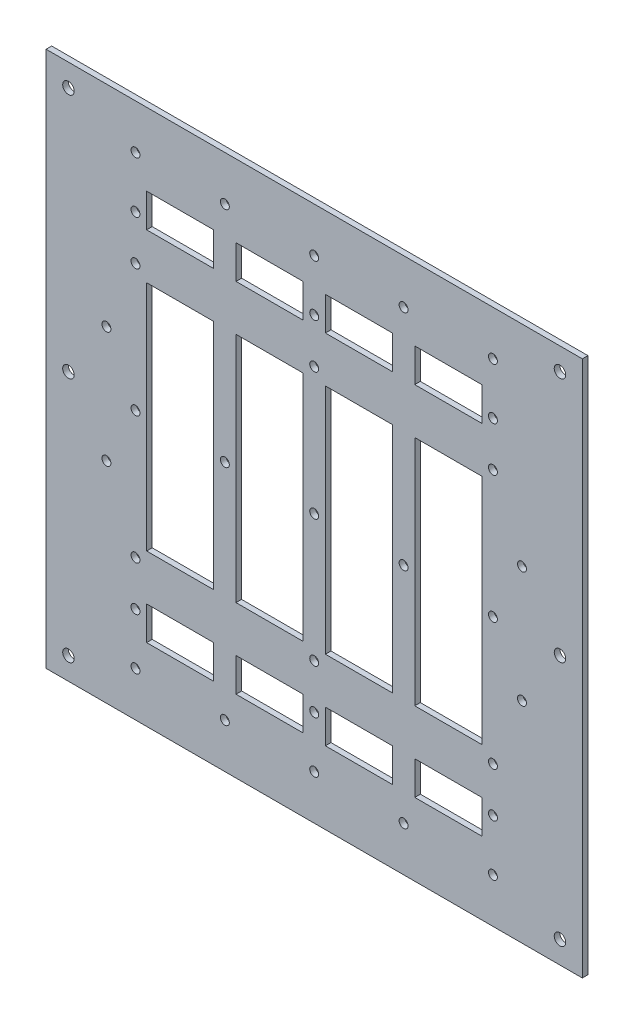
SolidWorks part; units mm, degrees
ref_plane "Front Plane" through (0, 0, 0) normal (0, 0, 1) x (1, 0, 0)
ref_plane "Top Plane" through (0, 0, 0) normal (0, 1, 0) x (1, 0, 0)
ref_plane "Right Plane" through (0, 0, 0) normal (1, 0, 0) x (0, 0, -1)
sketch "Sketch1" plane through (0, 0, 0) normal (0, 0, 1) x (1, 0, 0)
  line L0 (-152.4, 127) -> (-76.2, 127) construction
  line L1 (-152.4, 152.4) -> (152.4, 152.4)
  line L2 (-152.4, 152.4) -> (-152.4, -152.4)
  line L3 (-152.4, -152.4) -> (152.4, -152.4)
  line L4 (152.4, 152.4) -> (152.4, -152.4)
  line L5 (-76.2, 127) -> (-25.4, 127) construction
  line L6 (-25.4, 127) -> (25.4, 127) construction
  line L7 (25.4, 127) -> (76.2, 127) construction
  line L8 (76.2, 127) -> (152.4, 127) construction
  line L9 (-152.4, 0) -> (152.4, 0) construction
  line L10 (0, 152.4) -> (0, -152.4) construction
  line L11 (-118.11, 152.4) -> (-118.11, -152.4) construction
  line L12 (-152.4, -127) -> (152.4, -127) construction
  line L13 (127, 152.4) -> (127, -152.4) construction
  line L14 (-50.8, 152.4) -> (-50.8, -152.4) construction
  line L15 (50.8, 152.4) -> (50.8, -152.4) construction
  line L16 (-101.6, 152.4) -> (-101.6, -152.4) construction
  line L17 (-95.25, 66.04) -> (-57.15, 66.04)
  line L18 (-95.25, 66.04) -> (-95.25, -66.04)
  line L19 (-95.25, -66.04) -> (-57.15, -66.04)
  line L20 (-57.15, 66.04) -> (-57.15, -66.04)
  line L21 (-44.45, 66.04) -> (-6.35, 66.04)
  line L22 (-44.45, 66.04) -> (-44.45, -66.04)
  line L23 (-44.45, -66.04) -> (-6.35, -66.04)
  line L24 (-6.35, 66.04) -> (-6.35, -66.04)
  line L25 (6.35, 66.04) -> (44.45, 66.04)
  line L26 (6.35, 66.04) -> (6.35, -66.04)
  line L27 (6.35, -66.04) -> (44.45, -66.04)
  line L28 (44.45, 66.04) -> (44.45, -66.04)
  line L29 (57.15, 66.04) -> (95.25, 66.04)
  line L30 (57.15, 66.04) -> (57.15, -66.04)
  line L31 (57.15, -66.04) -> (95.25, -66.04)
  line L32 (95.25, 66.04) -> (95.25, -66.04)
  line L33 (101.6, 152.4) -> (101.6, -152.4) construction
  line L34 (-152.4, 120.65) -> (152.4, 120.65) construction
  line L35 (-101.6, 39.7057) -> (-95.25, 39.7057) construction
  line L36 (-57.15, 39.7057) -> (-50.8, 39.7057) construction
  line L37 (-76.2, 66.04) -> (-76.2, 0) construction
  line L38 (-76.2, 0) -> (-76.2, -66.04) construction
  line L39 (-152.4, 72.39) -> (152.4, 72.39) construction
  line L40 (-152.4, -72.39) -> (152.4, -72.39) construction
  line L41 (-76.2, 66.04) -> (-76.2, 72.39) construction
  line L42 (-95.25, -66.04) -> (-95.25, -72.39) construction
  line L43 (95.25, 39.7057) -> (101.6, 39.7057) construction
  line L44 (-95.25, 111.76) -> (-57.15, 111.76) construction
  line L45 (-57.15, 111.76) -> (-57.15, 118.4779) construction
  line L46 (-94.0266, 120.65) -> (-78.1749, 130.2582) construction
  line L47 (-95.25, 111.76) -> (-95.25, 118.4779) construction
  line L48 (-58.3734, 120.65) -> (-74.2251, 130.2582) construction
  line L49 (-107.3169, 130.81) -> (-83.1894, 130.81) construction
  line L50 (-6.35, 111.76) -> (-6.35, 118.4779) construction
  line L51 (-7.5734, 120.65) -> (-23.4251, 130.2582) construction
  line L52 (-43.2266, 120.65) -> (-27.3749, 130.2582) construction
  line L53 (-44.45, 111.76) -> (-44.45, 118.4779) construction
  line L54 (-6.35, 111.76) -> (-44.45, 111.76) construction
  line L55 (44.45, 111.76) -> (44.45, 118.4779) construction
  line L56 (43.2266, 120.65) -> (27.3749, 130.2582) construction
  line L57 (7.5734, 120.65) -> (23.4251, 130.2582) construction
  line L58 (6.35, 111.76) -> (6.35, 118.4779) construction
  line L59 (6.35, 111.76) -> (44.45, 111.76) construction
  line L60 (95.25, 111.76) -> (57.15, 111.76) construction
  line L61 (95.25, 111.76) -> (95.25, 118.4779) construction
  line L62 (94.0266, 120.65) -> (78.1749, 130.2582) construction
  line L63 (58.3734, 120.65) -> (74.2251, 130.2582) construction
  line L64 (57.15, 111.76) -> (57.15, 118.4779) construction
  line L65 (-95.25, -111.76) -> (-95.25, -118.4779) construction
  line L66 (-94.0266, -120.65) -> (-78.1749, -130.2582) construction
  line L67 (-58.3734, -120.65) -> (-74.2251, -130.2582) construction
  line L68 (-95.25, -111.76) -> (-57.15, -111.76) construction
  line L69 (-57.15, -111.76) -> (-57.15, -118.4779) construction
  line L70 (-44.45, -111.76) -> (-44.45, -118.4779) construction
  line L71 (-43.2266, -120.65) -> (-27.3749, -130.2582) construction
  line L72 (-6.35, -111.76) -> (-44.45, -111.76) construction
  line L73 (-7.5734, -120.65) -> (-23.4251, -130.2582) construction
  line L74 (-6.35, -111.76) -> (-6.35, -118.4779) construction
  line L75 (6.35, -111.76) -> (6.35, -118.4779) construction
  line L76 (7.5734, -120.65) -> (23.4251, -130.2582) construction
  line L77 (43.2266, -120.65) -> (27.3749, -130.2582) construction
  line L78 (6.35, -111.76) -> (44.45, -111.76) construction
  line L79 (44.45, -111.76) -> (44.45, -118.4779) construction
  line L80 (57.15, -111.76) -> (57.15, -118.4779) construction
  line L81 (58.3734, -120.65) -> (74.2251, -130.2582) construction
  line L82 (94.0266, -120.65) -> (78.1749, -130.2582) construction
  line L83 (95.25, -111.76) -> (57.15, -111.76) construction
  line L84 (95.25, -111.76) -> (95.25, -118.4779) construction
  line L85 (-152.4, 97.79) -> (152.4, 97.79) construction
  line L86 (-50.8, 39.7057) -> (-44.45, 39.7057) construction
  line L87 (-127, 152.4) -> (-127, -152.4) construction
  line L89 (-95.25, 101.6) -> (-92.3192, 101.6) construction
  line L90 (-95.25, 101.6) -> (-95.25, -101.6) construction
  line L96 (-90.8538, 101.6) -> (-90.8538, 68.58) construction
  line L97 (-89.3885, 101.6) -> (-89.3885, 68.58) construction
  line L98 (-92.3192, 101.6) -> (-92.3192, 68.58) construction
  line L99 (-83.5269, 101.6) -> (-83.5269, 68.58) construction
  line L100 (-86.4577, 101.6) -> (-86.4577, 68.58) construction
  line L101 (-89.3885, 101.6) -> (-86.4577, 101.6) construction
  line L102 (-77.6654, 101.6) -> (-77.6654, 68.58) construction
  line L103 (-80.5962, 101.6) -> (-80.5962, 68.58) construction
  line L104 (-83.5269, 101.6) -> (-80.5962, 101.6) construction
  line L105 (-71.8038, 101.6) -> (-71.8038, 68.58) construction
  line L106 (-74.7346, 101.6) -> (-74.7346, 68.58) construction
  line L107 (-77.6654, 101.6) -> (-74.7346, 101.6) construction
  line L108 (-65.9423, 101.6) -> (-65.9423, 68.58) construction
  line L109 (-68.8731, 101.6) -> (-68.8731, 68.58) construction
  line L110 (-71.8038, 101.6) -> (-68.8731, 101.6) construction
  line L111 (-60.0808, 101.6) -> (-60.0808, 68.58) construction
  line L112 (-63.0115, 101.6) -> (-63.0115, 68.58) construction
  line L113 (-65.9423, 101.6) -> (-63.0115, 101.6) construction
  line L114 (-57.15, -101.6) -> (-57.15, 101.6) construction
  line L115 (-60.0808, 101.6) -> (-57.15, 101.6) construction
  line L116 (-92.3192, 68.58) -> (-89.3885, 68.58) construction
  line L117 (-60.0808, -101.6) -> (-57.15, -101.6) construction
  line L118 (-60.0808, -101.6) -> (-60.0808, -68.58) construction
  line L119 (-63.0115, -101.6) -> (-63.0115, -68.58) construction
  line L120 (-65.9423, -101.6) -> (-65.9423, -68.58) construction
  line L121 (-65.9423, -101.6) -> (-63.0115, -101.6) construction
  line L122 (-68.8731, -101.6) -> (-68.8731, -68.58) construction
  line L123 (-71.8038, -101.6) -> (-68.8731, -101.6) construction
  line L124 (-71.8038, -101.6) -> (-71.8038, -68.58) construction
  line L125 (-74.7346, -101.6) -> (-74.7346, -68.58) construction
  line L126 (-77.6654, -101.6) -> (-74.7346, -101.6) construction
  line L127 (-77.6654, -101.6) -> (-77.6654, -68.58) construction
  line L128 (-80.5962, -101.6) -> (-80.5962, -68.58) construction
  line L129 (-83.5269, -101.6) -> (-80.5962, -101.6) construction
  line L130 (-83.5269, -101.6) -> (-83.5269, -68.58) construction
  line L131 (-86.4577, -101.6) -> (-86.4577, -68.58) construction
  line L132 (-89.3885, -101.6) -> (-86.4577, -101.6) construction
  line L133 (-89.3885, -101.6) -> (-89.3885, -68.58) construction
  line L134 (-92.3192, -101.6) -> (-92.3192, -68.58) construction
  line L135 (-95.25, -101.6) -> (-92.3192, -101.6) construction
  line L136 (-9.2808, 68.58) -> (-12.2115, 68.58) construction
  line L137 (6.35, 66.04) -> (44.45, 66.04) construction
  line L138 (-6.35, -66.04) -> (-6.35, -72.39) construction
  line L139 (-25.4, 66.04) -> (-25.4, 72.39) construction
  line L140 (-25.4, 0) -> (-25.4, -66.04) construction
  line L141 (-25.4, 66.04) -> (-25.4, 0) construction
  line L142 (-44.45, 66.04) -> (-44.45, -66.04) construction
  line L143 (-6.35, -66.04) -> (-44.45, -66.04) construction
  line L144 (-6.35, 66.04) -> (-6.35, -66.04) construction
  line L145 (-6.35, 66.04) -> (-44.45, 66.04) construction
  line L146 (-6.35, -101.6) -> (-9.2808, -101.6) construction
  line L147 (-9.2808, -101.6) -> (-9.2808, -68.58) construction
  line L148 (-12.2115, -101.6) -> (-12.2115, -68.58) construction
  line L149 (-12.2115, -101.6) -> (-15.1423, -101.6) construction
  line L150 (-15.1423, -101.6) -> (-15.1423, -68.58) construction
  line L151 (-18.0731, -101.6) -> (-18.0731, -68.58) construction
  line L152 (-18.0731, -101.6) -> (-21.0038, -101.6) construction
  line L153 (-21.0038, -101.6) -> (-21.0038, -68.58) construction
  line L154 (-23.9346, -101.6) -> (-23.9346, -68.58) construction
  line L155 (-23.9346, -101.6) -> (-26.8654, -101.6) construction
  line L156 (-26.8654, -101.6) -> (-26.8654, -68.58) construction
  line L157 (-29.7962, -101.6) -> (-29.7962, -68.58) construction
  line L158 (-29.7962, -101.6) -> (-32.7269, -101.6) construction
  line L159 (-32.7269, -101.6) -> (-32.7269, -68.58) construction
  line L160 (-35.6577, -101.6) -> (-38.5885, -101.6) construction
  line L161 (-35.6577, -101.6) -> (-35.6577, -68.58) construction
  line L162 (-38.5885, -101.6) -> (-38.5885, -68.58) construction
  line L163 (-41.5192, -101.6) -> (-41.5192, -68.58) construction
  line L164 (-41.5192, -101.6) -> (-44.45, -101.6) construction
  line L165 (-41.5192, 101.6) -> (-44.45, 101.6) construction
  line L166 (-44.45, -101.6) -> (-44.45, 101.6) construction
  line L167 (-35.6577, 101.6) -> (-38.5885, 101.6) construction
  line L168 (-38.5885, 101.6) -> (-38.5885, 68.58) construction
  line L169 (-41.5192, 101.6) -> (-41.5192, 68.58) construction
  line L170 (-29.7962, 101.6) -> (-32.7269, 101.6) construction
  line L171 (-32.7269, 101.6) -> (-32.7269, 68.58) construction
  line L172 (-35.6577, 101.6) -> (-35.6577, 68.58) construction
  line L173 (-23.9346, 101.6) -> (-26.8654, 101.6) construction
  line L174 (-26.8654, 101.6) -> (-26.8654, 68.58) construction
  line L175 (-29.7962, 101.6) -> (-29.7962, 68.58) construction
  line L176 (-18.0731, 101.6) -> (-21.0038, 101.6) construction
  line L177 (-21.0038, 101.6) -> (-21.0038, 68.58) construction
  line L178 (-23.9346, 101.6) -> (-23.9346, 68.58) construction
  line L179 (-12.2115, 101.6) -> (-15.1423, 101.6) construction
  line L180 (-15.1423, 101.6) -> (-15.1423, 68.58) construction
  line L181 (-18.0731, 101.6) -> (-18.0731, 68.58) construction
  line L182 (-9.2808, 101.6) -> (-9.2808, 68.58) construction
  line L183 (-12.2115, 101.6) -> (-12.2115, 68.58) construction
  line L184 (-6.35, 101.6) -> (-6.35, -101.6) construction
  line L185 (-6.35, 101.6) -> (-9.2808, 101.6) construction
  line L186 (6.35, 66.04) -> (6.35, -66.04) construction
  line L187 (6.35, -66.04) -> (44.45, -66.04) construction
  line L188 (44.45, 66.04) -> (44.45, -66.04) construction
  line L189 (25.4, 66.04) -> (25.4, 0) construction
  line L190 (25.4, 0) -> (25.4, -66.04) construction
  line L191 (25.4, 66.04) -> (25.4, 72.39) construction
  line L192 (6.35, -66.04) -> (6.35, -72.39) construction
  line L193 (9.2808, 68.58) -> (12.2115, 68.58) construction
  line L194 (6.35, 66.04) -> (6.35, -66.04) construction
  line L195 (44.45, -66.04) -> (6.35, -66.04) construction
  line L196 (44.45, 66.04) -> (44.45, -66.04) construction
  line L197 (44.45, 66.04) -> (6.35, 66.04) construction
  line L198 (6.35, 101.6) -> (9.2808, 101.6) construction
  line L199 (6.35, 101.6) -> (6.35, -101.6) construction
  line L200 (12.2115, 101.6) -> (12.2115, 68.58) construction
  line L201 (9.2808, 101.6) -> (9.2808, 68.58) construction
  line L202 (18.0731, 101.6) -> (18.0731, 68.58) construction
  line L203 (15.1423, 101.6) -> (15.1423, 68.58) construction
  line L204 (12.2115, 101.6) -> (15.1423, 101.6) construction
  line L205 (23.9346, 101.6) -> (23.9346, 68.58) construction
  line L206 (21.0038, 101.6) -> (21.0038, 68.58) construction
  line L207 (18.0731, 101.6) -> (21.0038, 101.6) construction
  line L208 (29.7962, 101.6) -> (29.7962, 68.58) construction
  line L209 (26.8654, 101.6) -> (26.8654, 68.58) construction
  line L210 (23.9346, 101.6) -> (26.8654, 101.6) construction
  line L211 (35.6577, 101.6) -> (35.6577, 68.58) construction
  line L212 (32.7269, 101.6) -> (32.7269, 68.58) construction
  line L213 (29.7962, 101.6) -> (32.7269, 101.6) construction
  line L214 (41.5192, 101.6) -> (41.5192, 68.58) construction
  line L215 (38.5885, 101.6) -> (38.5885, 68.58) construction
  line L216 (35.6577, 101.6) -> (38.5885, 101.6) construction
  line L217 (44.45, -101.6) -> (44.45, 101.6) construction
  line L218 (41.5192, 101.6) -> (44.45, 101.6) construction
  line L219 (41.5192, -101.6) -> (44.45, -101.6) construction
  line L220 (41.5192, -101.6) -> (41.5192, -68.58) construction
  line L221 (38.5885, -101.6) -> (38.5885, -68.58) construction
  line L222 (35.6577, -101.6) -> (35.6577, -68.58) construction
  line L223 (35.6577, -101.6) -> (38.5885, -101.6) construction
  line L224 (32.7269, -101.6) -> (32.7269, -68.58) construction
  line L225 (29.7962, -101.6) -> (32.7269, -101.6) construction
  line L226 (29.7962, -101.6) -> (29.7962, -68.58) construction
  line L227 (26.8654, -101.6) -> (26.8654, -68.58) construction
  line L228 (23.9346, -101.6) -> (26.8654, -101.6) construction
  line L229 (23.9346, -101.6) -> (23.9346, -68.58) construction
  line L230 (21.0038, -101.6) -> (21.0038, -68.58) construction
  line L231 (18.0731, -101.6) -> (21.0038, -101.6) construction
  line L232 (18.0731, -101.6) -> (18.0731, -68.58) construction
  line L233 (15.1423, -101.6) -> (15.1423, -68.58) construction
  line L234 (12.2115, -101.6) -> (15.1423, -101.6) construction
  line L235 (12.2115, -101.6) -> (12.2115, -68.58) construction
  line L236 (9.2808, -101.6) -> (9.2808, -68.58) construction
  line L237 (6.35, -101.6) -> (9.2808, -101.6) construction
  line L238 (57.15, 66.04) -> (95.25, 66.04) construction
  line L239 (57.15, 66.04) -> (57.15, -66.04) construction
  line L240 (57.15, -66.04) -> (95.25, -66.04) construction
  line L241 (95.25, 66.04) -> (95.25, -66.04) construction
  line L242 (92.3192, 68.58) -> (89.3885, 68.58) construction
  line L243 (95.25, -66.04) -> (95.25, -72.39) construction
  line L244 (76.2, 66.04) -> (76.2, 72.39) construction
  line L245 (76.2, 0) -> (76.2, -66.04) construction
  line L246 (76.2, 66.04) -> (76.2, 0) construction
  line L247 (57.15, 66.04) -> (57.15, -66.04) construction
  line L248 (95.25, -66.04) -> (57.15, -66.04) construction
  line L249 (95.25, 66.04) -> (95.25, -66.04) construction
  line L250 (95.25, 66.04) -> (57.15, 66.04) construction
  line L251 (57.15, 66.04) -> (57.15, -66.04) construction
  line L252 (95.25, -66.04) -> (57.15, -66.04) construction
  line L253 (95.25, 66.04) -> (95.25, -66.04) construction
  line L254 (95.25, 66.04) -> (57.15, 66.04) construction
  line L255 (95.25, -101.6) -> (92.3192, -101.6) construction
  line L256 (92.3192, -101.6) -> (92.3192, -68.58) construction
  line L257 (89.3885, -101.6) -> (89.3885, -68.58) construction
  line L258 (89.3885, -101.6) -> (86.4577, -101.6) construction
  line L259 (86.4577, -101.6) -> (86.4577, -68.58) construction
  line L260 (83.5269, -101.6) -> (83.5269, -68.58) construction
  line L261 (83.5269, -101.6) -> (80.5962, -101.6) construction
  line L262 (80.5962, -101.6) -> (80.5962, -68.58) construction
  line L263 (77.6654, -101.6) -> (77.6654, -68.58) construction
  line L264 (77.6654, -101.6) -> (74.7346, -101.6) construction
  line L265 (74.7346, -101.6) -> (74.7346, -68.58) construction
  line L266 (71.8038, -101.6) -> (71.8038, -68.58) construction
  line L267 (71.8038, -101.6) -> (68.8731, -101.6) construction
  line L268 (68.8731, -101.6) -> (68.8731, -68.58) construction
  line L269 (65.9423, -101.6) -> (63.0115, -101.6) construction
  line L270 (65.9423, -101.6) -> (65.9423, -68.58) construction
  line L271 (63.0115, -101.6) -> (63.0115, -68.58) construction
  line L272 (60.0808, -101.6) -> (60.0808, -68.58) construction
  line L273 (60.0808, -101.6) -> (57.15, -101.6) construction
  line L274 (60.0808, 101.6) -> (57.15, 101.6) construction
  line L275 (57.15, -101.6) -> (57.15, 101.6) construction
  line L276 (65.9423, 101.6) -> (63.0115, 101.6) construction
  line L277 (63.0115, 101.6) -> (63.0115, 68.58) construction
  line L278 (60.0808, 101.6) -> (60.0808, 68.58) construction
  line L279 (71.8038, 101.6) -> (68.8731, 101.6) construction
  line L280 (68.8731, 101.6) -> (68.8731, 68.58) construction
  line L281 (65.9423, 101.6) -> (65.9423, 68.58) construction
  line L282 (77.6654, 101.6) -> (74.7346, 101.6) construction
  line L283 (74.7346, 101.6) -> (74.7346, 68.58) construction
  line L284 (71.8038, 101.6) -> (71.8038, 68.58) construction
  line L285 (83.5269, 101.6) -> (80.5962, 101.6) construction
  line L286 (80.5962, 101.6) -> (80.5962, 68.58) construction
  line L287 (77.6654, 101.6) -> (77.6654, 68.58) construction
  line L288 (89.3885, 101.6) -> (86.4577, 101.6) construction
  line L289 (86.4577, 101.6) -> (86.4577, 68.58) construction
  line L290 (83.5269, 101.6) -> (83.5269, 68.58) construction
  line L291 (92.3192, 101.6) -> (92.3192, 68.58) construction
  line L292 (89.3885, 101.6) -> (89.3885, 68.58) construction
  line L293 (95.25, 101.6) -> (95.25, -101.6) construction
  line L294 (95.25, 101.6) -> (92.3192, 101.6) construction
  line L295 (-101.6, 39.7057) -> (-107.95, 39.7057) construction
  line L296 (-101.6, 78.74) -> (101.6, 78.74) construction
  line L297 (-107.95, 72.39) -> (-107.95, -72.39) construction
  line L298 (-101.6, -78.74) -> (101.6, -78.74) construction
  line L299 (107.95, 72.39) -> (107.95, -72.39) construction
  line L300 (-97.0611, 78.74) -> (-97.0611, 72.39) construction
  line L301 (-107.95, 22.225) -> (-120.65, 22.225) construction
  line L302 (-127, 15.875) -> (-127, -15.875) construction
  line L303 (-120.65, -22.225) -> (-107.95, -22.225) construction
  line L304 (-90.964, 120.65) -> (-61.436, 120.65) construction
  line L305 (-90.964, 122.2375) -> (-61.436, 122.2375) construction
  line L306 (-90.964, 119.0625) -> (-61.436, 119.0625) construction
  line L307 (-10.636, 120.65) -> (-40.164, 120.65) construction
  line L308 (-10.636, 122.2375) -> (-40.164, 122.2375) construction
  line L309 (-10.636, 119.0625) -> (-40.164, 119.0625) construction
  line L310 (10.636, 120.65) -> (40.164, 120.65) construction
  line L311 (10.636, 122.2375) -> (40.164, 122.2375) construction
  line L312 (10.636, 119.0625) -> (40.164, 119.0625) construction
  line L313 (90.964, 120.65) -> (61.436, 120.65) construction
  line L314 (90.964, 122.2375) -> (61.436, 122.2375) construction
  line L315 (90.964, 119.0625) -> (61.436, 119.0625) construction
  line L316 (90.964, -120.65) -> (61.436, -120.65) construction
  line L317 (90.964, -122.2375) -> (61.436, -122.2375) construction
  line L318 (90.964, -119.0625) -> (61.436, -119.0625) construction
  line L319 (10.636, -120.65) -> (40.164, -120.65) construction
  line L320 (10.636, -122.2375) -> (40.164, -122.2375) construction
  line L321 (10.636, -119.0625) -> (40.164, -119.0625) construction
  line L322 (-10.636, -120.65) -> (-40.164, -120.65) construction
  line L323 (-10.636, -122.2375) -> (-40.164, -122.2375) construction
  line L324 (-10.636, -119.0625) -> (-40.164, -119.0625) construction
  line L325 (-90.964, -120.65) -> (-61.436, -120.65) construction
  line L326 (-90.964, -122.2375) -> (-61.436, -122.2375) construction
  line L327 (-90.964, -119.0625) -> (-61.436, -119.0625) construction
  line L328 (-6.35, 111.125) -> (-6.35, 92.075)
  line L329 (-95.25, 111.125) -> (-57.15, 111.125)
  line L330 (-95.25, 111.125) -> (-95.25, 92.075)
  line L331 (-95.25, 92.075) -> (-57.15, 92.075)
  line L332 (-57.15, 111.125) -> (-57.15, 92.075)
  line L333 (-6.35, 111.125) -> (-44.45, 111.125)
  line L334 (-44.45, 111.125) -> (-44.45, 92.075)
  line L335 (-6.35, 92.075) -> (-44.45, 92.075)
  line L336 (95.25, 92.075) -> (57.15, 92.075)
  line L337 (95.25, 111.125) -> (95.25, 92.075)
  line L338 (95.25, 111.125) -> (57.15, 111.125)
  line L339 (57.15, 111.125) -> (57.15, 92.075)
  line L340 (44.45, 111.125) -> (44.45, 92.075)
  line L341 (6.35, 92.075) -> (44.45, 92.075)
  line L342 (6.35, 111.125) -> (44.45, 111.125)
  line L343 (6.35, 111.125) -> (6.35, 92.075)
  line L344 (-95.25, -92.075) -> (-57.15, -92.075)
  line L345 (-95.25, -111.125) -> (-95.25, -92.075)
  line L346 (-95.25, -111.125) -> (-57.15, -111.125)
  line L347 (-57.15, -111.125) -> (-57.15, -92.075)
  line L348 (-44.45, -111.125) -> (-44.45, -92.075)
  line L349 (-6.35, -92.075) -> (-44.45, -92.075)
  line L350 (-6.35, -111.125) -> (-44.45, -111.125)
  line L351 (-6.35, -111.125) -> (-6.35, -92.075)
  line L352 (6.35, -111.125) -> (6.35, -92.075)
  line L353 (6.35, -92.075) -> (44.45, -92.075)
  line L354 (6.35, -111.125) -> (44.45, -111.125)
  line L355 (44.45, -111.125) -> (44.45, -92.075)
  line L356 (57.15, -111.125) -> (57.15, -92.075)
  line L357 (95.25, -111.125) -> (57.15, -111.125)
  line L358 (95.25, -111.125) -> (95.25, -92.075)
  line L359 (95.25, -92.075) -> (57.15, -92.075)
  circle A0 centre (-76.2, 127) radius 2.5527 construction
  circle A1 centre (-25.4, 127) radius 2.5527 construction
  circle A2 centre (25.4, 127) radius 2.5527 construction
  circle A3 centre (76.2, 127) radius 2.5527 construction
  circle A4 centre (-101.6, 0) radius 2.54
  circle A5 centre (-50.8, 0) radius 2.54
  circle A6 centre (0, 0) radius 2.54
  circle A7 centre (101.6, 0) radius 2.54
  circle A8 centre (50.8, 0) radius 2.54
  circle A9 centre (-50.8, 127) radius 2.54
  circle A10 centre (0, 127) radius 2.54
  circle A11 centre (50.8, 127) radius 2.54
  circle A12 centre (-101.6, 72.39) radius 2.54
  circle A13 centre (0, 72.39) radius 2.54
  circle A14 centre (101.6, 72.39) radius 2.54
  circle A15 centre (-101.6, -72.39) radius 2.54
  circle A16 centre (0, -72.39) radius 2.54
  circle A17 centre (101.6, -72.39) radius 2.54
  arc A18 (-74.2251, 130.2582) -> (-78.1749, 130.2582) centre (-76.2, 127) ccw construction
  arc A19 (-57.15, 118.4779) -> (-58.3734, 120.65) centre (-59.69, 118.4779) ccw construction
  arc A20 (-95.25, 118.4779) -> (-94.0266, 120.65) centre (-92.71, 118.4779) cw construction
  arc A21 (-6.35, 118.4779) -> (-7.5734, 120.65) centre (-8.89, 118.4779) ccw construction
  arc A22 (-27.3749, 130.2582) -> (-23.4251, 130.2582) centre (-25.4, 127) cw construction
  arc A23 (-44.45, 118.4779) -> (-43.2266, 120.65) centre (-41.91, 118.4779) cw construction
  arc A24 (44.45, 118.4779) -> (43.2266, 120.65) centre (41.91, 118.4779) ccw construction
  arc A25 (27.3749, 130.2582) -> (23.4251, 130.2582) centre (25.4, 127) ccw construction
  arc A26 (6.35, 118.4779) -> (7.5734, 120.65) centre (8.89, 118.4779) cw construction
  arc A27 (95.25, 118.4779) -> (94.0266, 120.65) centre (92.71, 118.4779) ccw construction
  arc A28 (74.2251, 130.2582) -> (78.1749, 130.2582) centre (76.2, 127) cw construction
  arc A29 (57.15, 118.4779) -> (58.3734, 120.65) centre (59.69, 118.4779) cw construction
  circle A30 centre (-76.2, -127) radius 2.5527 construction
  circle A31 centre (-25.4, -127) radius 2.5527 construction
  circle A32 centre (25.4, -127) radius 2.5527 construction
  circle A33 centre (76.2, -127) radius 2.5527 construction
  arc A34 (-95.25, -118.4779) -> (-94.0266, -120.65) centre (-92.71, -118.4779) ccw construction
  arc A35 (-74.2251, -130.2582) -> (-78.1749, -130.2582) centre (-76.2, -127) cw construction
  arc A36 (-57.15, -118.4779) -> (-58.3734, -120.65) centre (-59.69, -118.4779) cw construction
  arc A37 (-44.45, -118.4779) -> (-43.2266, -120.65) centre (-41.91, -118.4779) ccw construction
  arc A38 (-27.3749, -130.2582) -> (-23.4251, -130.2582) centre (-25.4, -127) ccw construction
  arc A39 (-6.35, -118.4779) -> (-7.5734, -120.65) centre (-8.89, -118.4779) cw construction
  arc A40 (6.35, -118.4779) -> (7.5734, -120.65) centre (8.89, -118.4779) ccw construction
  arc A41 (27.3749, -130.2582) -> (23.4251, -130.2582) centre (25.4, -127) cw construction
  arc A42 (44.45, -118.4779) -> (43.2266, -120.65) centre (41.91, -118.4779) cw construction
  arc A43 (57.15, -118.4779) -> (58.3734, -120.65) centre (59.69, -118.4779) ccw construction
  arc A44 (74.2251, -130.2582) -> (78.1749, -130.2582) centre (76.2, -127) ccw construction
  arc A45 (95.25, -118.4779) -> (94.0266, -120.65) centre (92.71, -118.4779) cw construction
  circle A46 centre (50.8, -127) radius 2.54
  circle A47 centre (0, -127) radius 2.54
  circle A48 centre (-50.8, -127) radius 2.54
  circle A49 centre (-101.6, 97.79) radius 2.54
  circle A50 centre (0, 97.79) radius 2.54
  circle A51 centre (101.6, 97.79) radius 2.54
  circle A52 centre (101.6, 127) radius 2.54
  circle A53 centre (-101.6, 127) radius 2.54
  circle A54 centre (-118.11, 33.02) radius 2.54
  circle A56 centre (-101.6, -127) radius 2.54
  circle A57 centre (101.6, -127) radius 2.54
  circle A58 centre (101.6, -97.79) radius 2.54
  circle A59 centre (0, -97.79) radius 2.54
  circle A60 centre (-101.6, -97.79) radius 2.54
  circle A61 centre (-118.11, -33.02) radius 2.54
  circle A63 centre (-139.7, 139.7) radius 3.2639
  circle A64 centre (-139.7, 0) radius 3.2639
  circle A65 centre (-139.7, -139.7) radius 3.2639
  circle A66 centre (139.7, -139.7) radius 3.2639
  circle A67 centre (139.7, 0) radius 3.2639
  circle A68 centre (139.7, 139.7) radius 3.2639
  arc A70 (-92.3192, 68.58) -> (-89.3885, 68.58) centre (-90.8538, 68.58) ccw construction
  arc A71 (-86.4577, 68.58) -> (-83.5269, 68.58) centre (-84.9923, 68.58) ccw construction
  arc A72 (-80.5962, 68.58) -> (-77.6654, 68.58) centre (-79.1308, 68.58) ccw construction
  arc A73 (-74.7346, 68.58) -> (-71.8038, 68.58) centre (-73.2692, 68.58) ccw construction
  arc A74 (-68.8731, 68.58) -> (-65.9423, 68.58) centre (-67.4077, 68.58) ccw construction
  arc A75 (-63.0115, 68.58) -> (-60.0808, 68.58) centre (-61.5462, 68.58) ccw construction
  arc A76 (-63.0115, -68.58) -> (-60.0808, -68.58) centre (-61.5462, -68.58) cw construction
  arc A77 (-68.8731, -68.58) -> (-65.9423, -68.58) centre (-67.4077, -68.58) cw construction
  arc A78 (-74.7346, -68.58) -> (-71.8038, -68.58) centre (-73.2692, -68.58) cw construction
  arc A79 (-80.5962, -68.58) -> (-77.6654, -68.58) centre (-79.1308, -68.58) cw construction
  arc A80 (-86.4577, -68.58) -> (-83.5269, -68.58) centre (-84.9923, -68.58) cw construction
  arc A81 (-92.3192, -68.58) -> (-89.3885, -68.58) centre (-90.8538, -68.58) cw construction
  arc A82 (-9.2808, -68.58) -> (-12.2115, -68.58) centre (-10.7462, -68.58) ccw construction
  arc A83 (-15.1423, -68.58) -> (-18.0731, -68.58) centre (-16.6077, -68.58) ccw construction
  arc A84 (-21.0038, -68.58) -> (-23.9346, -68.58) centre (-22.4692, -68.58) ccw construction
  arc A85 (-26.8654, -68.58) -> (-29.7962, -68.58) centre (-28.3308, -68.58) ccw construction
  arc A86 (-32.7269, -68.58) -> (-35.6577, -68.58) centre (-34.1923, -68.58) ccw construction
  arc A87 (-38.5885, -68.58) -> (-41.5192, -68.58) centre (-40.0538, -68.58) ccw construction
  arc A88 (-38.5885, 68.58) -> (-41.5192, 68.58) centre (-40.0538, 68.58) cw construction
  arc A89 (-32.7269, 68.58) -> (-35.6577, 68.58) centre (-34.1923, 68.58) cw construction
  arc A90 (-26.8654, 68.58) -> (-29.7962, 68.58) centre (-28.3308, 68.58) cw construction
  arc A91 (-21.0038, 68.58) -> (-23.9346, 68.58) centre (-22.4692, 68.58) cw construction
  arc A92 (-15.1423, 68.58) -> (-18.0731, 68.58) centre (-16.6077, 68.58) cw construction
  arc A93 (-9.2808, 68.58) -> (-12.2115, 68.58) centre (-10.7462, 68.58) cw construction
  arc A94 (9.2808, 68.58) -> (12.2115, 68.58) centre (10.7462, 68.58) ccw construction
  arc A95 (15.1423, 68.58) -> (18.0731, 68.58) centre (16.6077, 68.58) ccw construction
  arc A96 (21.0038, 68.58) -> (23.9346, 68.58) centre (22.4692, 68.58) ccw construction
  arc A97 (26.8654, 68.58) -> (29.7962, 68.58) centre (28.3308, 68.58) ccw construction
  arc A98 (32.7269, 68.58) -> (35.6577, 68.58) centre (34.1923, 68.58) ccw construction
  arc A99 (38.5885, 68.58) -> (41.5192, 68.58) centre (40.0538, 68.58) ccw construction
  arc A100 (38.5885, -68.58) -> (41.5192, -68.58) centre (40.0538, -68.58) cw construction
  arc A101 (32.7269, -68.58) -> (35.6577, -68.58) centre (34.1923, -68.58) cw construction
  arc A102 (26.8654, -68.58) -> (29.7962, -68.58) centre (28.3308, -68.58) cw construction
  arc A103 (21.0038, -68.58) -> (23.9346, -68.58) centre (22.4692, -68.58) cw construction
  arc A104 (15.1423, -68.58) -> (18.0731, -68.58) centre (16.6077, -68.58) cw construction
  arc A105 (9.2808, -68.58) -> (12.2115, -68.58) centre (10.7462, -68.58) cw construction
  arc A106 (92.3192, -68.58) -> (89.3885, -68.58) centre (90.8538, -68.58) ccw construction
  arc A107 (86.4577, -68.58) -> (83.5269, -68.58) centre (84.9923, -68.58) ccw construction
  arc A108 (80.5962, -68.58) -> (77.6654, -68.58) centre (79.1308, -68.58) ccw construction
  arc A109 (74.7346, -68.58) -> (71.8038, -68.58) centre (73.2692, -68.58) ccw construction
  arc A110 (68.8731, -68.58) -> (65.9423, -68.58) centre (67.4077, -68.58) ccw construction
  arc A111 (63.0115, -68.58) -> (60.0808, -68.58) centre (61.5462, -68.58) ccw construction
  arc A112 (63.0115, 68.58) -> (60.0808, 68.58) centre (61.5462, 68.58) cw construction
  arc A113 (68.8731, 68.58) -> (65.9423, 68.58) centre (67.4077, 68.58) cw construction
  arc A114 (74.7346, 68.58) -> (71.8038, 68.58) centre (73.2692, 68.58) cw construction
  arc A115 (80.5962, 68.58) -> (77.6654, 68.58) centre (79.1308, 68.58) cw construction
  arc A116 (86.4577, 68.58) -> (83.5269, 68.58) centre (84.9923, 68.58) cw construction
  arc A117 (92.3192, 68.58) -> (89.3885, 68.58) centre (90.8538, 68.58) cw construction
  arc A118 (-101.6, 78.74) -> (-107.95, 72.39) centre (-101.6, 72.39) ccw construction
  arc A119 (-107.95, -72.39) -> (-101.6, -78.74) centre (-101.6, -72.39) ccw construction
  arc A120 (101.6, 78.74) -> (107.95, 72.39) centre (101.6, 72.39) cw construction
  arc A121 (101.6, -78.74) -> (107.95, -72.39) centre (101.6, -72.39) ccw construction
  arc A122 (-127, -15.875) -> (-120.65, -22.225) centre (-120.65, -15.875) ccw construction
  arc A123 (-120.65, 22.225) -> (-127, 15.875) centre (-120.65, 15.875) ccw construction
  arc A124 (-90.964, 122.2375) -> (-90.964, 119.0625) centre (-90.964, 120.65) ccw construction
  arc A125 (-61.436, 119.0625) -> (-61.436, 122.2375) centre (-61.436, 120.65) ccw construction
  arc A126 (-10.636, 122.2375) -> (-10.636, 119.0625) centre (-10.636, 120.65) cw construction
  arc A127 (-40.164, 119.0625) -> (-40.164, 122.2375) centre (-40.164, 120.65) cw construction
  arc A128 (10.636, 122.2375) -> (10.636, 119.0625) centre (10.636, 120.65) ccw construction
  arc A129 (40.164, 119.0625) -> (40.164, 122.2375) centre (40.164, 120.65) ccw construction
  arc A130 (90.964, 122.2375) -> (90.964, 119.0625) centre (90.964, 120.65) cw construction
  arc A131 (61.436, 119.0625) -> (61.436, 122.2375) centre (61.436, 120.65) cw construction
  arc A132 (90.964, -122.2375) -> (90.964, -119.0625) centre (90.964, -120.65) ccw construction
  arc A133 (61.436, -119.0625) -> (61.436, -122.2375) centre (61.436, -120.65) ccw construction
  arc A134 (10.636, -122.2375) -> (10.636, -119.0625) centre (10.636, -120.65) cw construction
  arc A135 (40.164, -119.0625) -> (40.164, -122.2375) centre (40.164, -120.65) cw construction
  arc A136 (-10.636, -122.2375) -> (-10.636, -119.0625) centre (-10.636, -120.65) ccw construction
  arc A137 (-40.164, -119.0625) -> (-40.164, -122.2375) centre (-40.164, -120.65) ccw construction
  arc A138 (-90.964, -122.2375) -> (-90.964, -119.0625) centre (-90.964, -120.65) cw construction
  arc A139 (-61.436, -119.0625) -> (-61.436, -122.2375) centre (-61.436, -120.65) cw construction
  circle A140 centre (118.11, -33.02) radius 2.54
  circle A141 centre (118.11, 33.02) radius 2.54
  point P10 (-76.2, 111.76)
  point P63 (50.8, 127)
  point P95 (-76.2, 66.04)
  point P97 (-25.4, 66.04)
  point P99 (25.4, 66.04)
  point P101 (76.2, 66.04)
  point P116 (-95.25, 0)
  point P118 (-44.45, 0)
  point P119 (6.35, 0)
  point P120 (57.15, 0)
  point P219 (-76.2, 33.02)
  point P259 (0, 78.74)
  point P260 (-107.95, 0)
  point P545 (-127, 0)
  point P548 (-127, -22.225)
  point P551 (-127, 22.225)
  point P554 (-76.2, 120.65)
  point P562 (-25.4, 120.65)
  point P569 (25.4, 120.65)
  point P576 (76.2, 120.65)
  point P583 (76.2, -120.65)
  point P590 (25.4, -120.65)
  point P597 (-25.4, -120.65)
  point P604 (-76.2, -120.65)
  point P612 (-57.15, 101.6)
  point P613 (-58.6154, 101.6)
  dimension "D1" = 5.1054
  dimension "D7" = 5.08
  dimension "D11" = 7.62
  dimension "D13" = 2.54
  dimension "D19" = 6.5278
  dimension "D25" = 6.35
  dimension "D26" = 6.35
  dimension "D27" = 6.35
  dimension "D29" = 6.35
  dimension "D2" = 25.4
  dimension "D3" = 50.8
  dimension "D4" = 25.4
  dimension "D5" = 25.4
  dimension "D6" = 25.4
  dimension "D8" = 38.1
  dimension "D9" = 31.75
  dimension "D10" = 132.08
  dimension "D12" = 19.05
  dimension "D14" = 25.4
  dimension "D15" = 304.8
  dimension "D16" = 304.8
  dimension "D17" = 8.89
  dimension "D18" = 12.7
  dimension "D20" = 12.7
  dimension "D21" = 12.7
  dimension "D23" = 33.02
  dimension "D24" = 10.16
  dimension "D28" = 44.45
  dimension "D30" = 3.175
  dimension "D31" = 19.05
  dimension "D22" = 6
extrude "Boss-Extrude1" add sketch "Sketch1" along normal blind 3.175 contours L4 L1 L2 L3 A67 A141 A60 A58 A56 A140 A54 A53 A52 A51 A50 A49 A47 L84 A45 L82 A44 L81 A43 L80 L83 L74 A39 L73 A38 L71 A37 L70 L72 L64 A29
